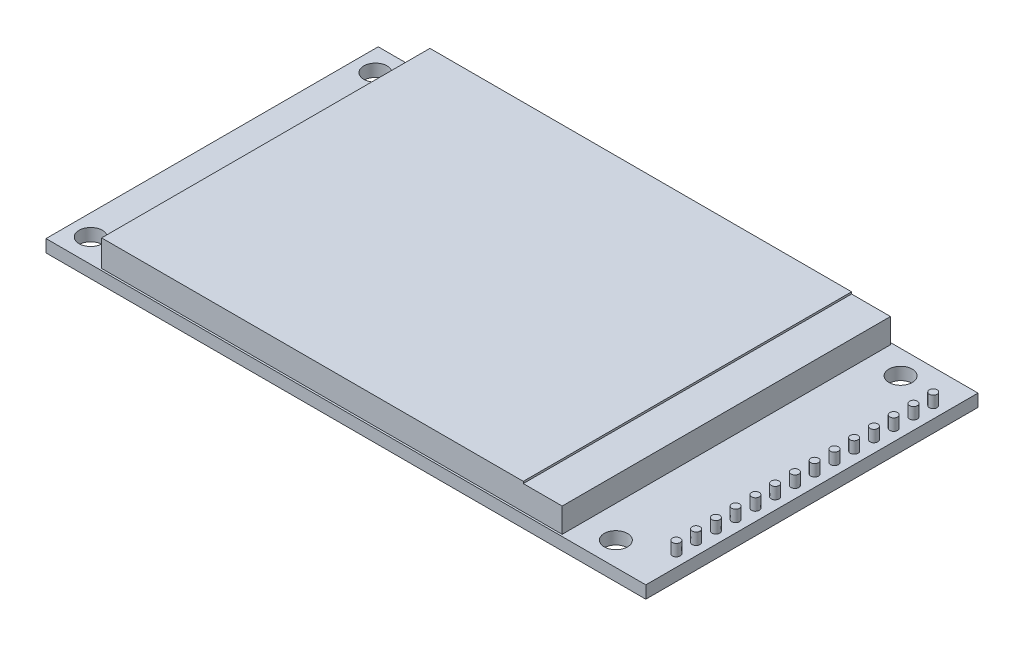
SolidWorks part; units mm, degrees
ref_plane "Front" through (0, 0, 0) normal (0, 0, 1) x (1, 0, 0)
ref_plane "Top" through (0, 0, 0) normal (0, 1, 0) x (1, 0, 0)
ref_plane "Right" through (0, 0, 0) normal (1, 0, 0) x (0, 0, -1)
sketch "Croquis1" plane through (0, 0, 0) normal (0, 1, 0) x (1, 0, 0)
  line L1 (38.55, -21.35) -> (-38.55, -21.35)
  line L2 (38.55, -21.35) -> (38.55, 21.35)
  line L3 (38.55, 21.35) -> (-38.55, 21.35)
  line L4 (-38.55, -21.35) -> (-38.55, 21.35)
  line L5 (38.55, -21.35) -> (-38.55, 21.35) construction
  line L6 (38.55, 21.35) -> (-38.55, -21.35) construction
  point P0 (0, 0)
  dimension "D1" = 77.1
  dimension "D2" = 42.7
extrude "Saliente-Extruir1" add sketch "Croquis1" along normal blind 1.6
sketch "Croquis2" plane through (0, 1.6, 0) normal (0, 1, 0) x (1, 0, 0)
  line L0 (-38.55, 21.35) -> (-38.55, -21.35) construction
  line L1 (27.55, -21.1) -> (-31.65, -21.1)
  line L2 (27.55, -21.1) -> (27.55, 21.1)
  line L3 (27.55, 21.1) -> (-31.65, 21.1)
  line L4 (-31.65, -21.1) -> (-31.65, 21.1)
  line L5 (27.55, -21.1) -> (-31.65, 21.1) construction
  line L6 (27.55, 21.1) -> (-31.65, -21.1) construction
  line L8 (38.55, -21.35) -> (38.55, 21.35) construction
  point P0 (-2.05, 0)
  dimension "D1" = 6.9
  dimension "D2" = 42.2
  dimension "D3" = 11
extrude "Saliente-Extruir2" add sketch "Croquis2" along normal offset from surface (3.4 mm away) 5 up to face at (0, 0, 0)
sketch "Croquis3" plane through (0, 1.6, 0) normal (0, 1, 0) x (1, 0, 0)
  line L0 (38.55, -21.35) -> (38.55, 21.35) construction
  circle A0 centre (37.05, -15.9232) radius 0.5
  circle A1 centre (37.05, -13.3832) radius 0.5
  circle A2 centre (37.05, -10.8432) radius 0.5
  circle A3 centre (37.05, -8.3032) radius 0.5
  circle A4 centre (37.05, -5.7632) radius 0.5
  circle A5 centre (37.05, -3.2232) radius 0.5
  circle A6 centre (37.05, -0.6832) radius 0.5
  circle A7 centre (37.05, 1.8568) radius 0.5
  circle A8 centre (37.05, 4.3968) radius 0.5
  circle A9 centre (37.05, 6.9368) radius 0.5
  circle A10 centre (37.05, 9.4768) radius 0.5
  circle A11 centre (37.05, 12.0168) radius 0.5
  circle A12 centre (37.05, 14.5568) radius 0.5
  circle A13 centre (37.05, 17.0968) radius 0.5
  dimension "D1" = 1
  dimension "D2" = 1.5
  dimension "D3" = 14
sketch "Croquis4" plane through (0, 0, 0) normal (0, -1, 0) x (1, 0, 0)
  line L0 (38.55, 21.35) -> (38.55, -21.35) construction
  line L1 (31.65, -18.3) -> (-35.85, -18.3) construction
  line L2 (31.65, -18.3) -> (31.65, 18.3) construction
  line L3 (31.65, 18.3) -> (-35.85, 18.3) construction
  line L4 (-35.85, -18.3) -> (-35.85, 18.3) construction
  line L5 (31.65, -18.3) -> (-35.85, 18.3) construction
  line L6 (31.65, 18.3) -> (-35.85, -18.3) construction
  circle A0 centre (-35.85, 18.3) radius 1.5
  circle A1 centre (31.65, 18.3) radius 1.5
  circle A2 centre (31.65, -18.3) radius 1.5
  circle A3 centre (-35.85, -18.3) radius 1.5
  point P0 (-2.1, 0)
  dimension "D1" = 3
  dimension "D2" = 67.5
  dimension "D3" = 36.6
  dimension "D4" = 6.9
extrude "Cortar-Extruir2" cut sketch "Croquis4" against normal up to next
sketch "Sketch3" plane through (0, 5, 0) normal (0, 1, 0) x (1, 0, 0)
  line L0 (22.55, 21.1005) -> (22.55, -21.1011)
  line L1 (-31.65, -21.1) -> (27.55, -21.1) construction
  line L2 (27.55, 21.1) -> (-31.65, 21.1) construction
  line L4 (27.55, -21.1) -> (27.55, 21.1) construction
  dimension "D1" = 5
extrude "Cut-Extrude1" cut sketch "Sketch3" against normal blind 0.25 and the other way through all
extrude "Boss-Extrude1" add sketch "Croquis3" along normal blind 1.5
